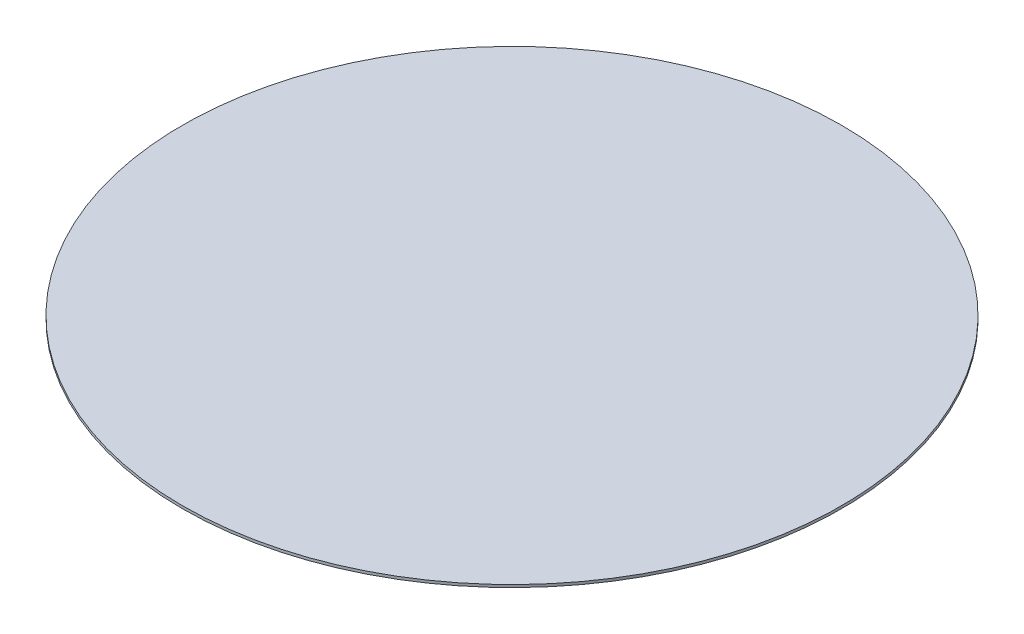
SolidWorks part; units mm, degrees
ref_plane "Front Plane" through (0, 0, 0) normal (0, 0, 1) x (1, 0, 0)
ref_plane "Top Plane" through (0, 0, 0) normal (0, 1, 0) x (1, 0, 0)
ref_plane "Right Plane" through (0, 0, 0) normal (1, 0, 0) x (0, 0, -1)
sketch "Sketch1" plane through (0, 0, 0) normal (0, 1, 0) x (1, 0, 0)
  circle A0 centre (0, 0) radius 95.25
  dimension "D1" = 190.5
extrude "Boss-Extrude1" add sketch "Sketch1" along normal blind 0.762
